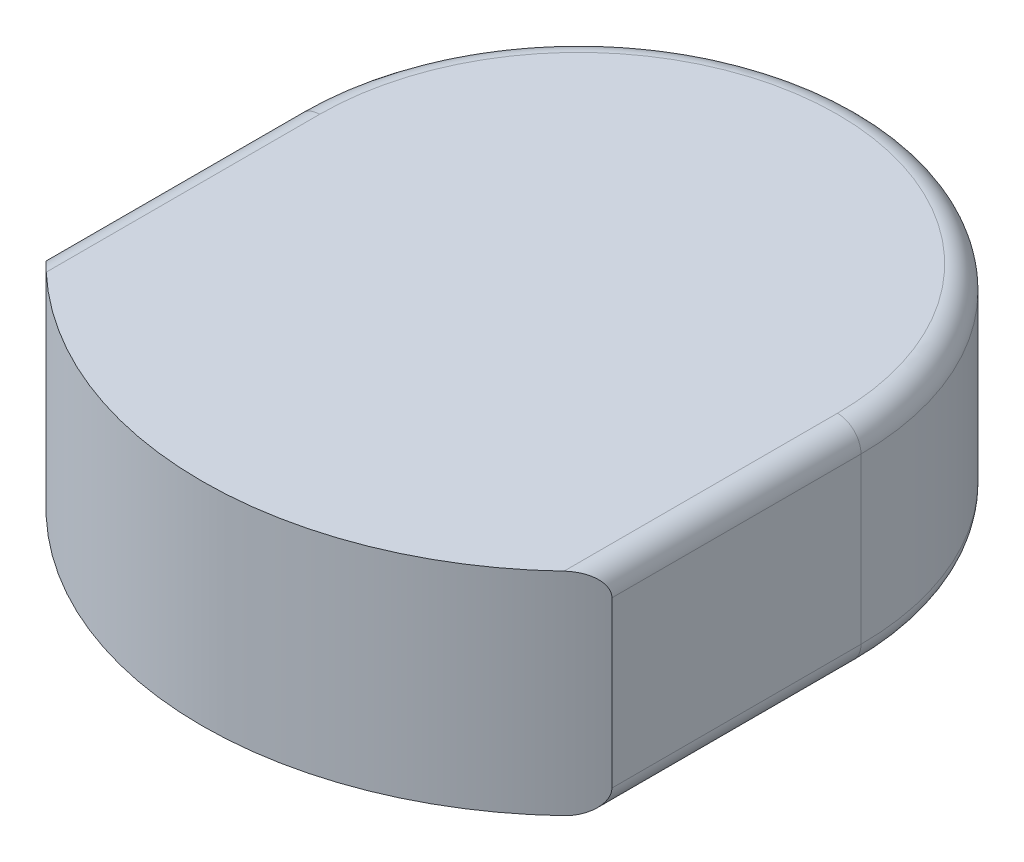
SolidWorks part; units mm, degrees
ref_plane "Front" through (0, 0, 0) normal (0, 0, 1) x (1, 0, 0)
ref_plane "Top" through (0, 0, 0) normal (0, 1, 0) x (1, 0, 0)
ref_plane "Right" through (0, 0, 0) normal (1, 0, 0) x (0, 0, -1)
sketch "Sketch1" plane through (0, 0, 0) normal (0, 1, 0) x (1, 0, 0)
  line L0 (0, -17.3479) -> (0, 8.6522) construction
  line L1 (-12, 20.6522) -> (-12, 10.0692)
  line L2 (12, 20.6522) -> (12, 10.0692)
  line L3 (0, 36.6522) -> (0, 45.5267) construction
  arc A0 (12, 20.6522) -> (-12, 20.6522) centre (0, 20.6522) ccw
  arc A1 (-12, 10.0692) -> (12, 10.0692) centre (0, 20.6522) ccw
  dimension "D1" = 24
  dimension "D2" = 32
extrude "Boss-Extrude1" add sketch "Sketch1" along normal blind 9
fillet "Fillet1" radius 1 6 edges at (12, 9, -15.3607) (-12, 9, -15.3607) (12, 0, -15.3607) (-12, 0, -15.3607) (0, 9, -32.6522) (0, 0, -32.6522)
